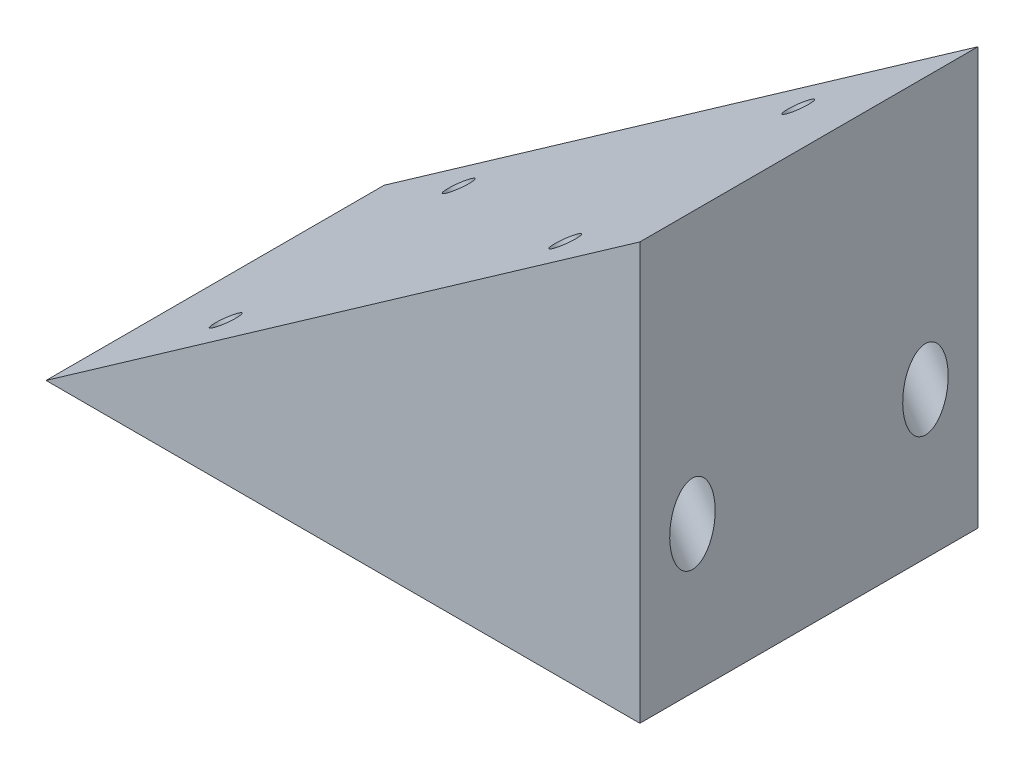
SolidWorks part; units mm, degrees
ref_plane "Front Plane" through (0, 0, 0) normal (0, 0, 1) x (1, 0, 0)
ref_plane "Top Plane" through (0, 0, 0) normal (0, 1, 0) x (1, 0, 0)
ref_plane "Right Plane" through (0, 0, 0) normal (1, 0, 0) x (0, 0, -1)
sketch "Sketch1" plane through (0, 0, 0) normal (0, 1, 0) x (1, 0, 0)
  line L1 (-52.25, -29.75) -> (52.25, -29.75)
  line L2 (-52.25, -29.75) -> (-52.25, 29.75)
  line L3 (-52.25, 29.75) -> (52.25, 29.75)
  line L4 (52.25, -29.75) -> (52.25, 29.75)
  line L5 (-52.25, -29.75) -> (52.25, 29.75) construction
  line L6 (-52.25, 29.75) -> (52.25, -29.75) construction
  point P0 (0, 0)
  dimension "D1" = 104.5
  dimension "D2" = 59.5
extrude "Boss-Extrude1" add sketch "Sketch1" along normal blind 73.36
sketch "Sketch6" plane through (0, 0, 29.75) normal (0, 0, 1) x (1, 0, 0)
  line L0 (-52.25, 0) -> (52.25, 73.36)
  line L1 (-52.25, 0) -> (-52.25, 73.36)
  line L2 (-52.25, 73.36) -> (52.25, 73.36)
extrude "Cut-Extrude2" cut sketch "Sketch6" against normal through all
ref_plane "Plane1" through (11.4792, -16.3519, 0) normal (0.5746, -0.8185, 0) x (-0.8185, -0.5746, 0)
sketch "Sketch8" plane through (11.4792, -16.3519, 0) normal (0.5746, -0.8185, 0) x (-0.8185, -0.5746, 0)
  line L0 (-57.5751, 20.5) -> (15.4249, 20.5) construction
  line L1 (15.4249, 20.5) -> (15.4249, -20.5) construction
  line L2 (15.4249, -20.5) -> (-57.5751, -20.5) construction
  line L3 (-57.5751, -20.5) -> (-57.5751, 20.5) construction
  line L4 (-57.5751, 20.5) -> (-84.9146, 20.5) construction
  line L5 (-84.9146, -29.75) -> (-84.9146, 29.75) construction
  line L6 (15.4249, 20.5) -> (42.7645, 20.5) construction
  line L7 (42.7645, 29.75) -> (42.7645, -29.75) construction
  line L8 (-57.5751, -20.5) -> (-57.5751, -29.75) construction
  line L9 (-84.9146, -29.75) -> (-42.7645, -29.75) construction
  line L10 (-57.5751, 29.75) -> (-57.5751, 20.5) construction
  line L11 (-84.9146, 29.75) -> (-42.7645, 29.75) construction
  point P17 (-57.5751, 20.5)
  point P18 (-57.5751, -20.5)
  point P19 (15.4249, -20.5)
  point P20 (15.4249, 20.5)
  dimension "D1" = 41
  dimension "D2" = 73
hole_wizard "CBORE for M4 SHCS1" positions "Sketch8" profile "Sketch9" counterbore size "M4" standard "ANSI Metric" end condition through all
sketch "Sketch9" plane through (-1.1455, -25.2146, -20.5) normal (0, 0, 1) x (0.8185, 0.5746, 0)
  line L0 (0, 0) -> (0, 110.0421)
  line L1 (0, 110.0421) -> (2.25, 110.0421)
  line L3 (2.25, 110.0421) -> (2.25, 44)
  line L4 (4, 44) -> (2.25, 44)
  line L5 (4, 44) -> (4, 0.021)
  line L6 (4, 0.021) -> (4.025, 0)
  line L7 (4.025, 0) -> (0, 0)
  line L8 (-4, 0.021) -> (-4.025, 0) construction
  line L11 (0, -6.35) -> (0, 107.95) construction
  dimension "Thru Hole Dia." = 4.5
  dimension "Thru Hole Depth" = 110.0421
  dimension "C'Bore Dia." = 8
  dimension "C'Bore Depth" = 44
  dimension "Near C'Sink Dia." = 8.05
  dimension "Near C'Sink Angle" = 100
